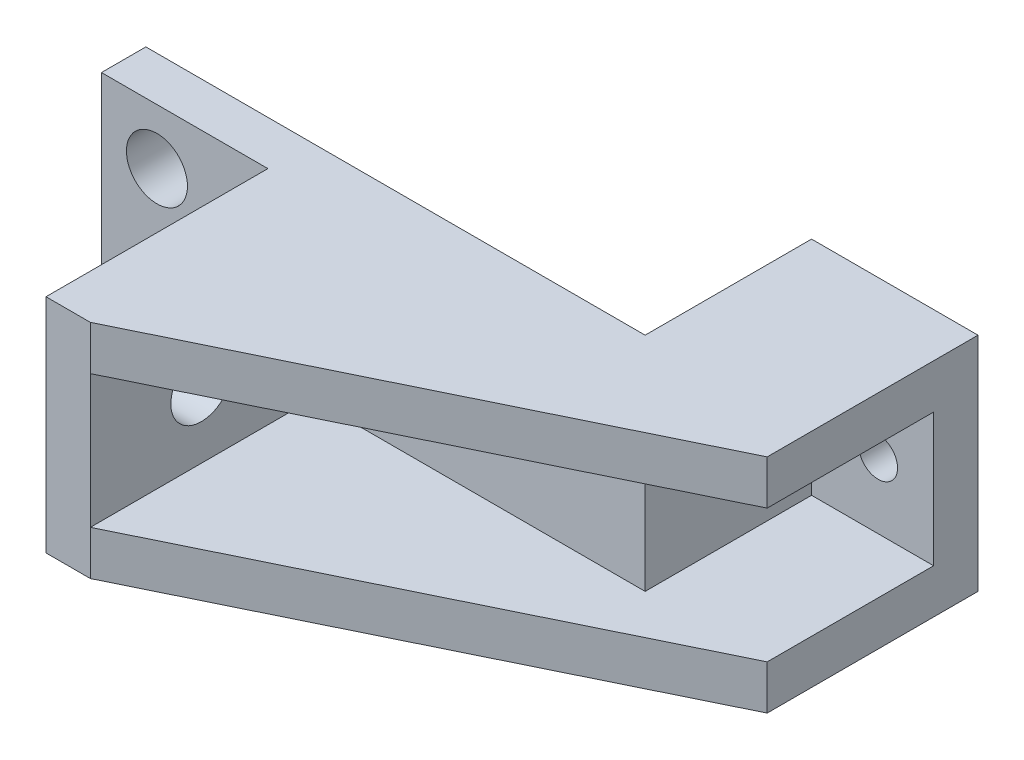
SolidWorks part; units mm, degrees
ref_plane "前视基准面" through (0, 0, 0) normal (0, 0, 1) x (1, 0, 0)
ref_plane "上视基准面" through (0, 0, 0) normal (0, 1, 0) x (1, 0, 0)
ref_plane "右视基准面" through (0, 0, 0) normal (1, 0, 0) x (0, 0, -1)
sketch "草图1" plane through (0, 0, 0) normal (0, 0, 1) x (1, 0, 0)
  line L1 (0, 0) -> (60, 0)
  line L2 (0, 0) -> (0, -20)
  line L3 (0, -20) -> (60, -20)
  line L4 (60, 0) -> (60, -20)
  circle A0 centre (5, -5) radius 2.75
  circle A1 centre (5, -15) radius 2.75
  circle A2 centre (55, -10) radius 1.75
  point P9 (0, -10)
  dimension "D3" = 5.5
  dimension "D4" = 5.5
  dimension "D5" = 10
  dimension "D6" = 5
  dimension "D7" = 5
  dimension "D8" = 5
  dimension "D9" = 3.5
  dimension "D10" = 10
  dimension "D11" = 5
  dimension "D1" = 60
  dimension "D2" = 20
extrude "凸台-拉伸1" add sketch "草图1" along normal blind 4
sketch "草图2" plane through (0, 0, 0) normal (0, 0, -1) x (-1, 0, 0)
  line L0 (-60, 0) -> (0, 0) construction
  line L1 (-15, 0) -> (-19, 0)
  line L2 (-15, 0) -> (-15, -20)
  line L3 (-15, -20) -> (-19, -20)
  line L4 (-19, 0) -> (-19, -20)
  line L5 (0, -20) -> (-60, -20) construction
  line L6 (0, 0) -> (0, -20) construction
  dimension "D1" = 15
  dimension "D2" = 4
extrude "凸台-拉伸2" add sketch "草图2" against normal blind 24
sketch "草图3" plane through (0, -20, 0) normal (0, -1, 0) x (1, 0, 0)
  line L0 (19, 24) -> (60, 4)
  line L1 (60, 4) -> (19, 4)
  line L2 (19, 4) -> (19, 24)
  line L3 (19, 24) -> (19.006, 24.0158)
  line M1 (60, 4) -> (19, 4)
  line M2 (19, 4) -> (19, 24)
extrude "凸台-拉伸3" add sketch "草图3" against normal blind 4 contours L0 M2 M1
sketch "草图4" plane through (0, 0, 0) normal (0, 1, 0) x (1, 0, 0)
  line L3 (19, -24) -> (60, -4)
  line L4 (60, -4) -> (19, -4)
  line L5 (19, -4) -> (19, -24)
  line L6 (19, -24) -> (60, -4)
  line L7 (60, -4) -> (19, -4)
  line L8 (19, -4) -> (19, -24)
  dimension "D1" = 0
extrude "凸台-拉伸4" add sketch "草图4" against normal blind 4
sketch "草图5" plane through (0, 0, 0) normal (0, 0, -1) x (-1, 0, 0)
  line L0 (-60, 0) -> (0, 0) construction
  line L1 (-60, -20) -> (-15, -20)
  line L2 (-60, -20) -> (-60, 0)
  line L3 (-60, 0) -> (-15, 0)
  line L4 (-15, -20) -> (-15, 0)
  circle A0 centre (-55, -10) radius 1.75
  dimension "D1" = 45
extrude "凸台-拉伸5" add sketch "草图5" along normal blind 15
sketch "草图6" plane through (0, 0, 4) normal (0, 0, 1) x (1, 0, 0)
  line L0 (60, -4) -> (19, -4) construction
  line L1 (60, -16) -> (20, -16)
  line L2 (60, -16) -> (60, -4)
  line L3 (60, -4) -> (20, -4)
  line L4 (20, -16) -> (20, -4)
  dimension "D1" = 40
extrude "切除-拉伸1" cut sketch "草图6" against normal blind 15
sketch "草图7" plane through (19, 0, 0) normal (1, 0, 0) x (0, 0, -1)
  line L0 (-24, -4) -> (-24, -16) construction
  line L1 (-24, -16) -> (-4, -16) construction
  circle A0 centre (-14, -10) radius 2.75
  dimension "D1" = 5.5
  dimension "D2" = 10
  dimension "D3" = 6
extrude "切除-拉伸2" cut sketch "草图7" against normal blind 15
sketch "草图8" plane through (0, 0, -15) normal (0, 0, -1) x (-1, 0, 0)
  line L0 (-15, -20) -> (-15, 0) construction
  line L1 (-15, -20) -> (-45, -20)
  line L2 (-15, -20) -> (-15, 0)
  line L3 (-15, 0) -> (-45, 0)
  line L4 (-45, -20) -> (-45, 0)
  line L5 (-15, -20) -> (-15, 0) construction
  line L6 (-15, 0) -> (-60, 0) construction
  dimension "D1" = 30
extrude "切除-拉伸3" cut sketch "草图8" against normal up to surface (15 mm away) up to face at (7.75, -5, 0)
sketch "草图10" plane through (0, 0, 4) normal (0, 0, 1) x (1, 0, 0)
  line L1 (19, -4) -> (45, -4)
  line L2 (19, -4) -> (19, -16)
  line L3 (19, -16) -> (45, -16)
  line L4 (45, -4) -> (45, -16)
extrude "凸台-拉伸6" add sketch "草图10" against normal up to surface (4 mm away) up to face at (7.75, -5, 0)
sketch "草图11" plane through (45, 0, 0) normal (1, 0, 0) x (0, 0, -1)
  line L1 (-4, -16) -> (11, -16)
  line L2 (-4, -16) -> (-4, -4)
  line L3 (-4, -4) -> (11, -4)
  line L4 (11, -16) -> (11, -4)
extrude "凸台-拉伸7" add sketch "草图11" along normal blind 4
